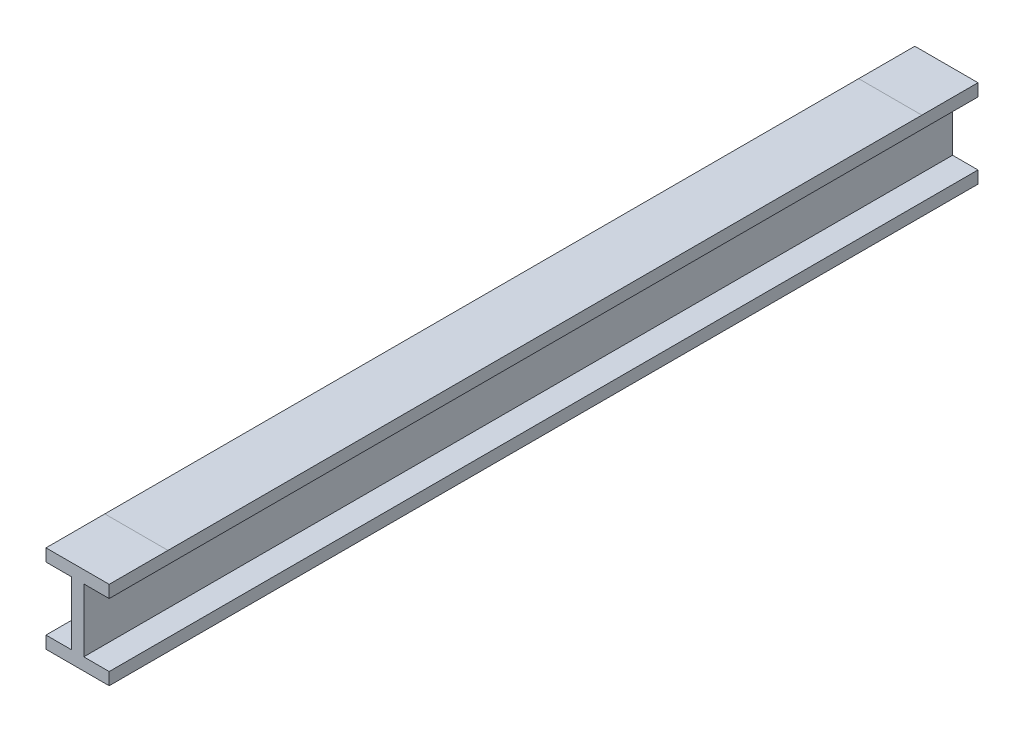
SolidWorks part; units mm, degrees
ref_plane "Płaszczyzna przednia" through (0, 0, 0) normal (0, 0, 1) x (1, 0, 0)
ref_plane "Płaszczyzna górna" through (0, 0, 0) normal (0, 1, 0) x (1, 0, 0)
ref_plane "Płaszczyzna prawa" through (0, 0, 0) normal (1, 0, 0) x (0, 0, -1)
sketch "Szkic1" plane through (0, 0, 0) normal (0, 0, 1) x (1, 0, 0)
  line L0 (0, 0) -> (160, 0)
  line L1 (160, 0) -> (160, 31.25)
  line L2 (160, 31.25) -> (95.625, 31.25)
  line L3 (95.625, 31.25) -> (95.625, 191.25)
  line L4 (95.625, 191.25) -> (160, 191.25)
  line L5 (160, 191.25) -> (160, 222.5)
  line L6 (160, 222.5) -> (0, 222.5)
  line L7 (0, 222.5) -> (0, 191.25)
  line L8 (0, 191.25) -> (64.375, 191.25)
  line L9 (64.375, 191.25) -> (64.375, 31.25)
  line L10 (64.375, 31.25) -> (0, 31.25)
  line L11 (0, 31.25) -> (0, 0)
  dimension "D1" = 160
  dimension "D2" = 160
  dimension "D3" = 222.5
  dimension "D5" = 64.375
extrude "Dodanie-wyciągnięcie1" add sketch "Szkic1" along normal blind 2200
sketch "Szkic2" plane through (0, 222.5, 0) normal (0, 1, 0) x (1, 0, 0)
  line L0 (0, -142.1977) -> (160, -142.1977)
  line L1 (0, -2200) -> (0, 0) construction
  line L2 (160, -2200) -> (160, 0) construction
  line L3 (0, -2051.1393) -> (160, -2051.1393)
split line "Linia podziałowa1"
